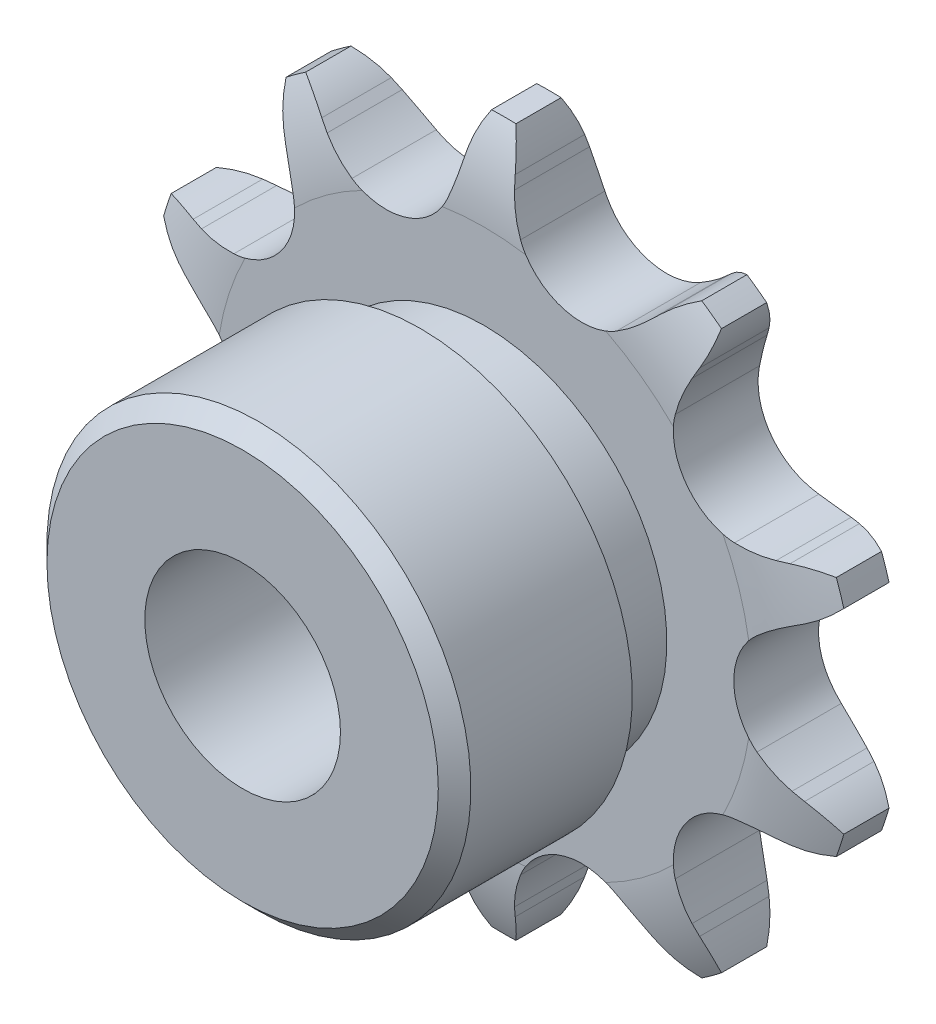
SolidWorks part; units mm, degrees
ref_plane "Front Plane" through (0, 0, 0) normal (0, 0, 1) x (1, 0, 0)
ref_plane "Top Plane" through (0, 0, 0) normal (0, 1, 0) x (1, 0, 0)
ref_plane "Right Plane" through (0, 0, 0) normal (1, 0, 0) x (0, 0, -1)
sketch "Sketch0" plane through (0, 0, 0) normal (0, 0, 1) x (1, 0, 0)
  line L0 (3, -9.2331) -> (0, 0) construction
  line L1 (0, 0) -> (7.8541, -5.7063) construction
  line L2 (0, 0) -> (-3, -9.2331) construction
  line L3 (3, -9.2331) -> (7.8541, -5.7063) construction
  line L4 (3, -9.2331) -> (-3, -9.2331) construction
  line L5 (5.207, -8.3985) -> (4.9578, -8.1628)
  line L6 (3, -9.2331) -> (0, -10.2078) construction
  line L7 (0.724, -9.8551) -> (0.7871, -9.518)
  line L8 (0, -9.2331) -> (0, -11.0331) construction
  line L9 (4.0548, -7.4775) -> (1.3519, -11.976) construction
  line L10 (0, 0) -> (0, -9.2331) construction
  line L11 (4.9578, -8.1628) -> (1.3519, -11.976) construction
  line L12 (0, -11.0331) -> (0, -11.3954) construction
  line L13 (7.5305, -5.9415) -> (5.207, -8.3985) construction
  circle A0 centre (0, 0) radius 11.0331 construction
  circle A1 centre (0, 0) radius 9.7082 construction
  arc A2 (-3.5166, -12.4881) -> (10.1854, -8.0361) centre (0, 0) ccw
  circle A3 centre (0, 0) radius 11.3954 construction
  circle A4 centre (3, -9.2331) radius 2 construction
  arc A7 (4.0548, -7.4775) -> (1.1147, -8.4328) centre (3, -9.2331) ccw
  circle A8 centre (3, -9.2331) radius 2.0481 construction
  arc A9 (5.207, -8.3985) -> (10.1854, -8.0361) centre (7.5305, -5.9415) ccw
  arc A10 (4.9578, -8.1628) -> (4.0548, -7.4775) centre (1.3519, -11.976) ccw
  arc A11 (0.724, -9.8551) -> (-3.5166, -12.4881) centre (-2.6, -9.2331) cw
  arc A12 (0.7871, -9.518) -> (1.1147, -8.4328) centre (5.9456, -10.4834) cw
  dimension "D1" = 2.0481
  dimension "R" = 2.0481
sketch "Sketch1" plane through (0, 0, 0) normal (1, 0, 0) x (0, 0, -1)
  line L0 (1.3, 0) -> (-1.3, 0)
  line L1 (-1.3, 0) -> (-1.3, 8.2206)
  line L2 (-1.3, 9.7082) -> (0, 9.7082) construction
  line L3 (-0.6, 11.0331) -> (0.6, 11.0331)
  line L5 (1.3, 8.2206) -> (1.3, 0)
  line L7 (0, 11.0331) -> (0, 0) construction
  line L8 (-1.3, 8.2206) -> (1.3, 8.2206) construction
  line L9 (0, 11.0331) -> (0, -11.0331) construction
  line L10 (-1.3, 8.2206) -> (-1.3, 11.0331) construction
  line L11 (-1.3, 11.0331) -> (-0.6, 11.0331) construction
  line L12 (0.6, 11.0331) -> (1.3, 11.0331) construction
  line L13 (1.3, 11.0331) -> (1.3, 8.2206) construction
  line L14 (0, 0) -> (-6.4008, 0) construction
  line L15 (-1.3, 9.7082) -> (-1.3, 5.6082) construction
  line L22 (1.3, 0) -> (-8.7, 0) construction
  line L24 (-1.3, 0) -> (-1.3, 5.6082) construction
  arc A0 (-0.6, 11.0331) -> (-1.3, 8.2206) centre (4.7, 8.2206) ccw
  arc A1 (0.6, 11.0331) -> (1.3, 8.2206) centre (-4.7, 8.2206) cw
  dimension "R" = 6
revolve "Revolve1" add sketch "Sketch1" angle 360 mid plane about L0
extrude "Cut-Extrude1" cut sketch "Sketch0" against normal through all and the other way through all
pattern_circular "CirPattern1" count 10 over 360 about axis through (0, 0, 0) along (0, 0, 1) of "Cut-Extrude1"
sketch "Sketch2" plane through (0, 0, 0) normal (0, 0, 1) x (1, 0, 0)
  circle A0 centre (0, 0) radius 3 construction
  circle A1 centre (0, 0) radius 6.5
  circle A2 centre (0, 0) radius 10.85 construction
  dimension "Bore" = 6
  dimension "Hub Dia." = 13
  dimension "OD" = 21.7
extrude "Boss-Extrude1" add sketch "Sketch2" along normal up to vertex (8.7 mm away) from surface at 1.3 starting at face at (0, 0, 1.3)
sketch "Sketch3" plane through (0, 0, 0) normal (0, 0, 1) x (1, 0, 0)
  circle A0 centre (0, 0) radius 3 construction
  circle A1 centre (0, 0) radius 3
extrude "Cut-Extrude2" cut sketch "Sketch3" along normal through all and the other way through all
sketch "Sketch4" plane through (0, 0, 0) normal (1, 0, 0) x (0, 0, -1)
  line L0 (-8.7, 6.5) -> (-8.7, 6)
  line L1 (-1.3, 11.0331) -> (-3.25, 11.0331)
  line L2 (-1.3, 11.0331) -> (-1.3, 5.6082)
  line L3 (-1.3, 5.6082) -> (-3.25, 5.6082)
  line L4 (-3.25, 11.0331) -> (-3.25, 5.6082)
  line L9 (-8.7, 6) -> (-8.2, 6.5)
  line L10 (-8.2, 6.5) -> (-8.7, 6.5)
  dimension "C" = 0.5
  dimension "D3" = 1.95
revolve "Cut-Revolve1" cut sketch "Sketch4" angle 360 mid plane about L22
sketch "Sketch5" plane through (0, 0, 0) normal (0, 0, 1) x (1, 0, 0)
  circle A0 centre (0, 0) radius 10.85 construction
  circle A1 centre (0, 0) radius 10.85
extrude "Cut-Extrude3" cut sketch "Sketch5" against normal through all and the other way through all flip side to cut
equation "\"360/N@Sketch0\" = 360/\"Teeth@CirPattern1\""
equation "\"Ds@Sketch0\" = 1.005 * \"Dr@Sketch0\" + ( 0.003 * 25.4 ) "
equation "\"R@Sketch0\" = 1/2 * \"Ds@Sketch0\""
equation "\"A@Sketch0\" = 35 +  ( 60 / \"Teeth@CirPattern1\" ) "
equation "\"B@Sketch0\" = 18 -  ( 56 / \"Teeth@CirPattern1\" )"
equation "\"ac@Sketch0\" = 0.8 * \"Dr@Sketch0\""
equation "\"ab@Sketch0\" = 1.4 * \"Dr@Sketch0\""
equation "\"J@Sketch0\" = 0.3 * \"Pitch@Sketch0\""
equation "\"D3@Sketch4\" = \"t@Sketch1\" * 3 / 4"
